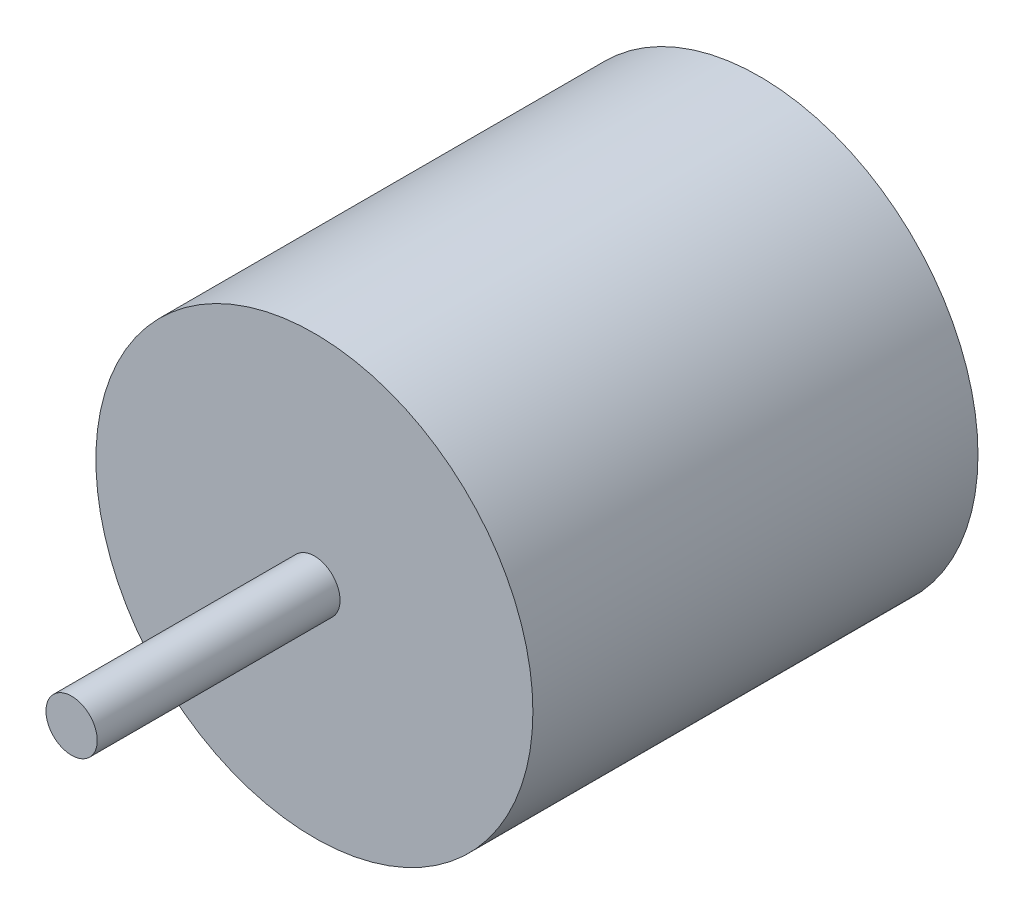
SolidWorks part; units mm, degrees
ref_plane "Front Plane" through (0, 0, 0) normal (0, 0, 1) x (1, 0, 0)
ref_plane "Top Plane" through (0, 0, 0) normal (0, 1, 0) x (1, 0, 0)
ref_plane "Right Plane" through (0, 0, 0) normal (1, 0, 0) x (0, 0, -1)
sketch "Sketch1" plane through (0, 0, 0) normal (0, 0, 1) x (1, 0, 0)
  circle A0 centre (0, 0) radius 13.5
  dimension "D1" = 27
extrude "Boss-Extrude1" add sketch "Sketch1" along normal blind 27.5
sketch "Sketch2" plane through (0, 0, 27.5) normal (0, 0, 1) x (1, 0, 0)
  circle A0 centre (0, 0) radius 1.585
  dimension "D1" = 3.17
extrude "Boss-Extrude2" add sketch "Sketch2" along normal blind 15
